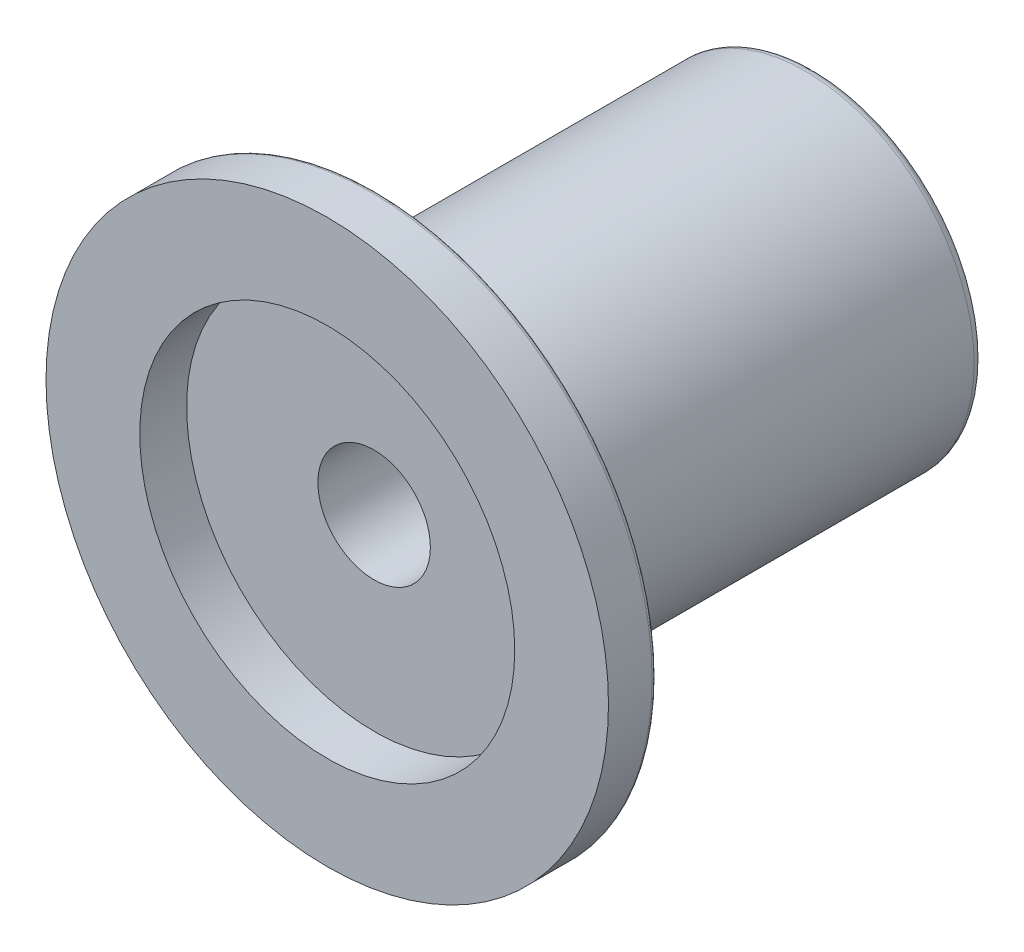
SolidWorks part; units mm, degrees
ref_plane "Front Plane" through (0, 0, 0) normal (0, 0, 1) x (1, 0, 0)
ref_plane "Top Plane" through (0, 0, 0) normal (0, 1, 0) x (1, 0, 0)
ref_plane "Right Plane" through (0, 0, 0) normal (1, 0, 0) x (0, 0, -1)
sketch "Sketch1" plane through (0, 0, 0) normal (1, 0, 0) x (0, 0, -1)
  line L0 (0, 0) -> (-10.0711, 0) construction
  line L1 (0, 10) -> (0, 15)
  line L2 (23.5, 0) -> (26, 0)
  line L3 (0, 0) -> (0, 10) construction
  line L4 (4.8589, 9) -> (25.5, 9)
  line L5 (26, 0) -> (26, 8.5)
  line L6 (0, 15) -> (2.3249, 15)
  line L7 (2.5599, 14.8355) -> (4.624, 9.1645)
  line L8 (0, 10) -> (2.5, 10)
  line L9 (2.5, 10) -> (2.5, 3)
  line L10 (2.5, 3) -> (23.5, 3)
  line L11 (23.5, 3) -> (23.5, 0)
  line L12 (0, 0) -> (23.5, 0) construction
  arc A0 (25.5, 9) -> (26, 8.5) centre (25.5, 8.5) cw
  arc A1 (4.624, 9.1645) -> (4.8589, 9) centre (4.8589, 9.25) ccw
  arc A2 (2.3249, 15) -> (2.5599, 14.8355) centre (2.3249, 14.75) cw
  point P19 (2.5, 15)
  dimension "D10" = 0.5
  dimension "D11" = 0.25
  dimension "D1" = 26
  dimension "D2" = 30
  dimension "D3" = 18
  dimension "D4" = 6
  dimension "D5" = 2.5
  dimension "D6" = 20
  dimension "D7" = 2.5
  dimension "D8" = 20
  dimension "D9" = 2.5
revolve "Revolve1" add sketch "Sketch1" angle 360 about L12
sketch "Sketch2" plane through (0, 0, -26) normal (0, 0, -1) x (-1, 0, 0)
  line L0 (0, 0) -> (0, 8) construction
  line L2 (-0.125, 9.5) -> (0.125, 9.5)
  line L3 (-0.125, 9.5) -> (-0.125, 6.5)
  line L4 (-0.125, 6.5) -> (0.125, 6.5)
  line L5 (0.125, 9.5) -> (0.125, 6.5)
  line L6 (-0.125, 9.5) -> (0.125, 6.5) construction
  line L7 (-0.125, 6.5) -> (0.125, 9.5) construction
  dimension "D1" = 0.25
  dimension "D2" = 8
  dimension "D3" = 3
extrude "Cut-Extrude1" cut sketch "Sketch2" against normal blind 0.25
